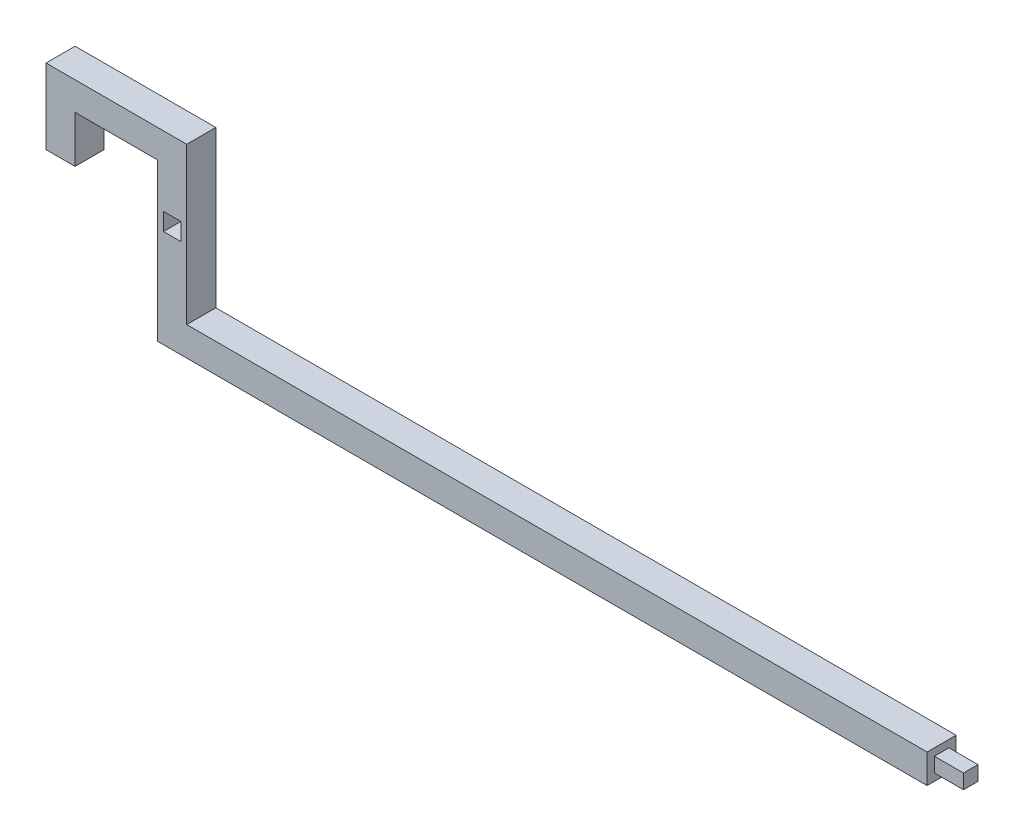
SolidWorks part; units mm, degrees
ref_plane "Front Plane" through (0, 0, 0) normal (0, 0, 1) x (1, 0, 0)
ref_plane "Top Plane" through (0, 0, 0) normal (0, 1, 0) x (1, 0, 0)
ref_plane "Right Plane" through (0, 0, 0) normal (1, 0, 0) x (0, 0, -1)
sketch "Sketch1" plane through (0, 0, 0) normal (0, 0, 1) x (1, 0, 0)
  line L0 (0, 6.7) -> (0, 8.05)
  line L5 (0, 0) -> (-5, 0)
  line L6 (-5, 0) -> (-5, 12.9)
  line L7 (-5, 12.9) -> (5.5, 12.9)
  line L8 (0, 8.05) -> (5.5, 8.05)
  line L10 (5.5, 12.9) -> (19.2, 12.9)
  line L11 (5.5, 8.05) -> (14.2, 8.05)
  line L16 (0, 6.7) -> (0, 0)
  line L17 (14.2, 8.05) -> (14.2, -18.95)
  line L18 (14.2, -18.95) -> (146.5, -18.95)
  line L19 (19.2, 12.9) -> (19.2, -13.95)
  line L20 (146.5, -18.95) -> (146.5, -13.95)
  line L21 (19.2, -13.95) -> (146.5, -13.95)
  dimension "D1" = 6.7
  dimension "D2" = 27
  dimension "D3" = 1.35
  dimension "D4" = 5
  dimension "D5" = 4.85
  dimension "D6" = 5
  dimension "D7" = 14.2
  dimension "D8" = 4.85
  dimension "D9" = 5
  dimension "D10" = 5
  dimension "D13" = 6.7
  dimension "D16" = 132.3
extrude "Boss-Extrude1" add sketch "Sketch1" along normal blind 5
sketch "Sketch2" plane through (146.5, 0, 0) normal (1, 0, 0) x (0, 0, -1)
  line L0 (-5, -18.95) -> (-5, -13.95) construction
  line L1 (-3.75, -17.7) -> (-1.25, -17.7)
  line L2 (-3.75, -17.7) -> (-3.75, -15.2)
  line L3 (-3.75, -15.2) -> (-1.25, -15.2)
  line L4 (-1.25, -17.7) -> (-1.25, -15.2)
  line L6 (-5, -13.95) -> (0, -13.95) construction
  point P4 (-3.75, -16.45)
  dimension "D1" = 2.5
  dimension "D2" = 2.5
  dimension "D3" = 1.25
  dimension "D4" = 1.25
extrude "Boss-Extrude2" add sketch "Sketch2" along normal blind 5
sketch "Sketch3" plane through (0, 0, 5) normal (0, 0, 1) x (1, 0, 0)
  line L0 (14.2, 8.05) -> (14.2, -18.95) construction
  line L1 (15.2, 0.9) -> (18.2, 0.9)
  line L2 (15.2, 0.9) -> (15.2, -2.1)
  line L3 (15.2, -2.1) -> (18.2, -2.1)
  line L4 (18.2, 0.9) -> (18.2, -2.1)
  line L5 (19.2, 12.9) -> (-5, 12.9) construction
  dimension "D1" = 3
  dimension "D2" = 3
  dimension "D3" = 1
  dimension "D4" = 12
extrude "Cut-Extrude1" cut sketch "Sketch3" against normal blind 10
